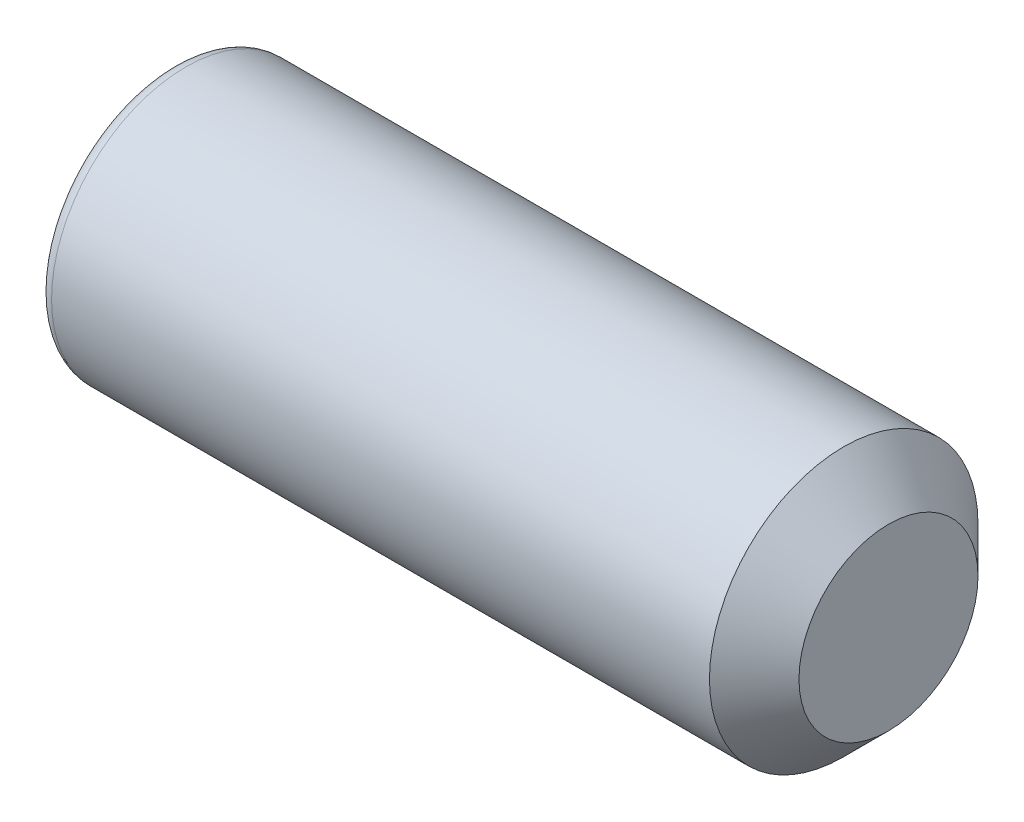
SolidWorks part; units mm, degrees
ref_plane "Front Plane" through (0, 0, 0) normal (0, 0, 1) x (1, 0, 0)
ref_plane "Top Plane" through (0, 0, 0) normal (0, 1, 0) x (1, 0, 0)
ref_plane "Right Plane" through (0, 0, 0) normal (1, 0, 0) x (0, 0, -1)
sketch "Sketch1" plane through (0, 0, 0) normal (0, 0, 1) x (1, 0, 0)
  line L0 (0, 0) -> (0, 1.5)
  line L1 (0, -1.65) -> (0, 1.65) construction
  line L2 (0, 1.5) -> (7.5, 1.5)
  line L3 (7.5, 1.5) -> (8, 1)
  line L4 (8, 1) -> (8, 0)
  line L5 (1.65, 0) -> (-1.65, 0) construction
  line L6 (8, 0) -> (0, 0)
  dimension "D1" = 1.5
  dimension "D2" = 8
  dimension "D3" = 45
  dimension "D4" = 1
revolve "Revolve1" add sketch "Sketch1" angle 360 about L6
sketch "Sketch2" plane through (0, 0, 0) normal (-1, 0, 0) x (0, 0, 1)
  line L1 (0.433, 0.75) -> (-0.433, 0.75)
  line L2 (-0.433, 0.75) -> (-0.866, 0)
  line L3 (-0.866, 0) -> (-0.433, -0.75)
  line L4 (-0.433, -0.75) -> (0.433, -0.75)
  line L5 (0.433, -0.75) -> (0.866, 0)
  line L6 (0.866, 0) -> (0.433, 0.75)
  circle A0 centre (0, 0) radius 0.75 construction
  dimension "D1" = 1.5
extrude "Cut-Extrude1" cut sketch "Sketch2" against normal blind 1.2
fillet "Fillet1" radius 0.15 1 edges at (0, 0, -1.5)
equation "\"d\"=3"
equation "\"s\"= 1.5"
equation "\"t\"= 1.2"
equation "\"l\"= 8"
equation "\"dp\"= 2"
equation "\"D1@Sketch1\"=\"d\" / 2"
equation "\"D2@Sketch1\"=\"l\""
equation "\"D4@Sketch1\"=\"dp\" / 2"
equation "\"D1@Sketch2\"=\"s\""
equation "\"D1@Cut-Extrude1\"=\"t\""
equation "\"D1@Fillet1\"=\"d\" / 20"
